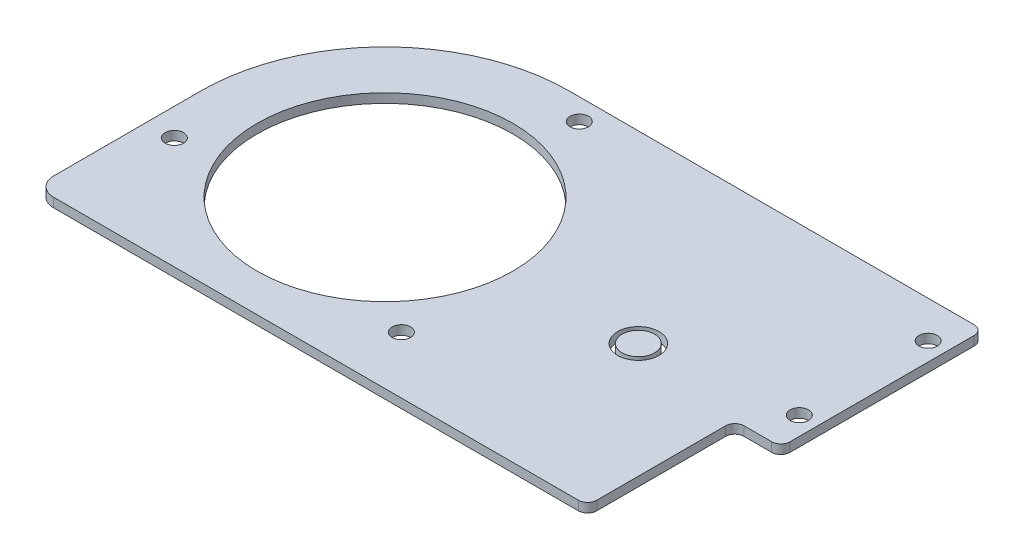
SolidWorks part; units mm, degrees
ref_plane "Front Plane" through (0, 0, 0) normal (0, 0, 1) x (1, 0, 0)
ref_plane "Top Plane" through (0, 0, 0) normal (0, 1, 0) x (1, 0, 0)
ref_plane "Right Plane" through (0, 0, 0) normal (1, 0, 0) x (0, 0, -1)
sketch "Sketch1" plane through (0, 0, 0) normal (0, 1, 0) x (1, 0, 0)
  line L0 (0, 114.3) -> (0, -101.6) construction
  line L1 (279.4, 127) -> (0, 127)
  line L2 (285.75, 120.65) -> (285.75, -6.35)
  line L3 (247.65, -114.3) -> (-114.3, -114.3)
  line L4 (-127, 0) -> (-127, -101.6)
  line L5 (260.35, -12.7) -> (279.4, -12.7)
  line L6 (273.05, -12.7) -> (273.05, 127) construction
  line L7 (-127, 0) -> (285.75, 0) construction
  line L8 (0, 0) -> (-127, -43.7296) construction
  line L11 (254, -107.95) -> (254, -19.05)
  circle A0 centre (0, 0) radius 88.265
  circle A1 centre (0, 0) radius 114.3 construction
  circle A2 centre (-108.0728, -37.2124) radius 6.35
  arc A3 (260.35, -12.7) -> (254, -19.05) centre (260.35, -19.05) ccw
  arc A4 (-127, 0) -> (0, 127) centre (0, 0) cw
  circle A5 centre (21.8095, 112.2) radius 6.35
  circle A6 centre (86.2633, -74.9875) radius 6.35
  arc A7 (-114.3, -114.3) -> (-127, -101.6) centre (-114.3, -101.6) cw
  arc A8 (247.65, -114.3) -> (254, -107.95) centre (247.65, -107.95) ccw
  arc A9 (285.75, -6.35) -> (279.4, -12.7) centre (279.4, -6.35) cw
  arc A10 (279.4, 127) -> (285.75, 120.65) centre (279.4, 120.65) cw
  circle A11 centre (273.05, 101.6) radius 6.35
  circle A12 centre (273.05, 12.7) radius 6.35
  point P0 (0, 0)
  point P11 (0, 0)
  point P32 (254, -114.3)
  point P46 (0, 0)
  dimension "D3" = 176.53
  dimension "D5" = 228.6
  dimension "D6" = 12.7
  dimension "D7" = 127
  dimension "D8" = 101.6
  dimension "D11" = 31.75
  dimension "D12" = 25.4
  dimension "D14" = 12.7
  dimension "D9" = 6.35
  dimension "D10" = 12.7
  dimension "D1" = 127
  dimension "D2" = 114.3
  dimension "D4" = 19
  dimension "D13" = 12.7
  dimension "D15" = 25.4
  dimension "D16" = 412.75
extrude "Boss-Extrude1" add sketch "Sketch1" along normal blind 6.35
sketch "Sketch3" plane through (0, 6.35, 0) normal (0, 1, 0) x (1, 0, 0)
  line L0 (79.375, 127) -> (79.375, -114.3) construction
  line L5 (382.3904, 6.35) -> (-202.4477, 6.35) construction
  line L6 (339.725, -158.75) -> (-180.975, -158.75)
  line L7 (339.725, -158.75) -> (339.725, 171.45)
  line L8 (339.725, 171.45) -> (-180.975, 171.45)
  line L9 (-180.975, -158.75) -> (-180.975, 171.45)
  line L10 (339.725, -158.75) -> (-180.975, 171.45) construction
  line L11 (339.725, 171.45) -> (-180.975, -158.75) construction
  line L26 (285.75, -6.35) -> (285.75, 120.65) construction
  line L27 (-127, 0) -> (-127, -101.6) construction
  line L28 (-114.3, -114.3) -> (247.65, -114.3) construction
  line L29 (279.4, 127) -> (0, 127) construction
  line L30 (285.75, -6.35) -> (285.75, 120.65)
  line L31 (-127, 0) -> (-127, -101.6)
  line L32 (-114.3, -114.3) -> (247.65, -114.3)
  line L33 (279.4, 127) -> (0, 127)
  point P1 (79.375, 6.35)
  dimension "D1" = 520.7
  dimension "D2" = 206.375
  dimension "D3" = 330.2
  dimension "D4" = 120.65
  dimension "D7" = 412.75
  dimension "D8" = 241.3
sketch "Sketch5" plane through (0, 0, 0) normal (0, 1, 0) x (1, 0, 0)
  circle A1 centre (162.3238, 0) radius 11.176 construction
sketch "Sketch6" plane through (0, 0, 0) normal (0, 1, 0) x (1, 0, 0)
  circle A0 centre (174.752, 0) radius 14.2875
  circle A2 centre (174.752, 0) radius 11.176
  circle A3 centre (174.752, 0) radius 11.176 construction
  circle A4 centre (174.752, 0) radius 11.176 construction
  dimension "D1" = 28.575
extrude "Cut-Extrude1" cut sketch "Sketch6" along normal blind 28.448
